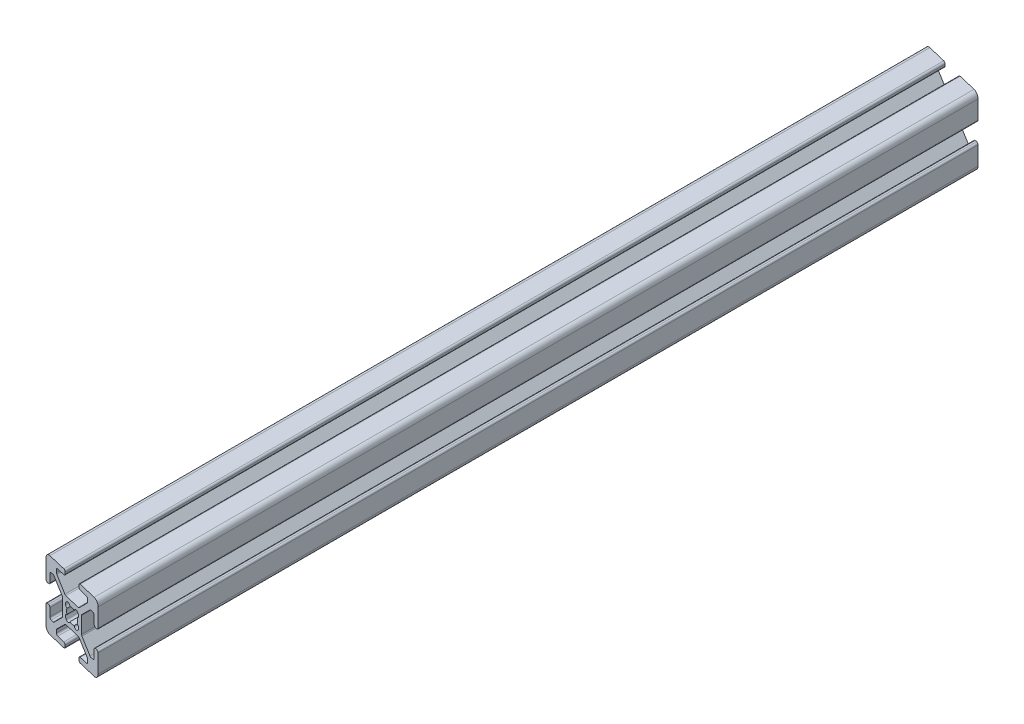
SolidWorks part; units mm, degrees
material "Alumina"
ref_plane "Front Plane" through (0, 0, 0) normal (0, 0, 1) x (1, 0, 0)
ref_plane "Top Plane" through (0, 0, 0) normal (0, 1, 0) x (1, 0, 0)
ref_plane "Right Plane" through (0, 0, 0) normal (1, 0, 0) x (0, 0, -1)
ref_plane "Plane1" through (0, 0, 4000) normal (0, 0, 1) x (1, 0, 0)
sketch "Sketch1" plane through (0, 0, 4000) normal (0, 0, 1) x (1, 0, 0)
  line B0 (10, 3.138) -> (10, 8.5)
  line B1 (8.5, 10) -> (3.138, 10)
  line B2 (2.63, 9.492) -> (2.63, 9.008)
  line B3 (3.138, 8.5) -> (5.487, 8.5)
  line B4 (5.995, 7.992) -> (5.995, 7.2661)
  line B5 (5.8462, 6.9069) -> (2.7431, 3.8038)
  line B6 (2.3839, 3.655) -> (-2.3839, 3.655)
  line B7 (-2.7431, 3.8038) -> (-5.8462, 6.9069)
  line B8 (-5.995, 7.2661) -> (-5.995, 7.992)
  line B9 (-5.487, 8.5) -> (-3.138, 8.5)
  line B10 (-2.63, 9.008) -> (-2.63, 9.492)
  line B11 (-3.138, 10) -> (-8.5, 10)
  line B12 (-10, 8.5) -> (-10, 3.138)
  line B13 (-9.492, 2.63) -> (-9.008, 2.63)
  line B14 (-8.5, 3.138) -> (-8.5, 5.487)
  line B15 (-7.992, 5.995) -> (-7.2661, 5.995)
  line B16 (-6.9069, 5.8462) -> (-3.8038, 2.7431)
  line B17 (-3.655, 2.3839) -> (-3.655, -2.3839)
  line B18 (-3.8038, -2.7431) -> (-6.9069, -5.8462)
  line B19 (-7.2661, -5.995) -> (-7.992, -5.995)
  line B20 (-8.5, -5.487) -> (-8.5, -3.138)
  line B21 (-9.008, -2.63) -> (-9.492, -2.63)
  line B22 (-10, -3.138) -> (-10, -8.5)
  line B23 (-8.5, -10) -> (-3.138, -10)
  line B24 (-2.63, -9.492) -> (-2.63, -9.008)
  line B25 (-3.138, -8.5) -> (-5.487, -8.5)
  line B26 (-5.995, -7.992) -> (-5.995, -7.2661)
  line B27 (-5.8462, -6.9069) -> (-2.7431, -3.8038)
  line B28 (-2.3839, -3.655) -> (2.3839, -3.655)
  line B29 (2.7431, -3.8038) -> (5.8462, -6.9069)
  line B30 (5.995, -7.2661) -> (5.995, -7.992)
  line B31 (5.487, -8.5) -> (3.138, -8.5)
  line B32 (2.63, -9.008) -> (2.63, -9.492)
  line B33 (3.138, -10) -> (8.5, -10)
  line B34 (10, -8.5) -> (10, -3.138)
  line B35 (9.492, -2.63) -> (9.008, -2.63)
  line B36 (8.5, -3.138) -> (8.5, -5.487)
  line B37 (7.992, -5.995) -> (7.2661, -5.995)
  line B38 (6.9069, -5.8462) -> (3.8038, -2.7431)
  line B39 (3.655, -2.3839) -> (3.655, 2.3839)
  line B40 (3.8038, 2.7431) -> (6.9069, 5.8462)
  line B41 (7.2661, 5.995) -> (7.992, 5.995)
  line B42 (8.5, 5.487) -> (8.5, 3.138)
  line B43 (9.008, 2.63) -> (9.492, 2.63)
  line B44 (-2.1249, -2.3045) -> (-2.3045, -2.1249)
  line B45 (-2.3045, 2.1249) -> (-2.1249, 2.3045)
  line B46 (2.1249, 2.3045) -> (2.3045, 2.1249)
  line B47 (2.3045, -2.1249) -> (2.1249, -2.3045)
  arc B48 (9.492, 2.63) -> (10, 3.138) centre (9.492, 3.138) ccw
  arc B49 (10, 8.5) -> (8.5, 10) centre (8.5, 8.5) ccw
  arc B50 (3.138, 10) -> (2.63, 9.492) centre (3.138, 9.492) ccw
  arc B51 (2.63, 9.008) -> (3.138, 8.5) centre (3.138, 9.008) ccw
  arc B52 (5.487, 8.5) -> (5.995, 7.992) centre (5.487, 7.992) cw
  arc B53 (5.995, 7.2661) -> (5.8462, 6.9069) centre (5.487, 7.2661) cw
  arc B54 (2.7431, 3.8038) -> (2.3839, 3.655) centre (2.3839, 4.163) cw
  arc B55 (-2.3839, 3.655) -> (-2.7431, 3.8038) centre (-2.3839, 4.163) cw
  arc B56 (-5.8462, 6.9069) -> (-5.995, 7.2661) centre (-5.487, 7.2661) cw
  arc B57 (-5.995, 7.992) -> (-5.487, 8.5) centre (-5.487, 7.992) cw
  arc B58 (-3.138, 8.5) -> (-2.63, 9.008) centre (-3.138, 9.008) ccw
  arc B59 (-2.63, 9.492) -> (-3.138, 10) centre (-3.138, 9.492) ccw
  arc B60 (-8.5, 10) -> (-10, 8.5) centre (-8.5, 8.5) ccw
  arc B61 (-10, 3.138) -> (-9.492, 2.63) centre (-9.492, 3.138) ccw
  arc B62 (-9.008, 2.63) -> (-8.5, 3.138) centre (-9.008, 3.138) ccw
  arc B63 (-8.5, 5.487) -> (-7.992, 5.995) centre (-7.992, 5.487) cw
  arc B64 (-7.2661, 5.995) -> (-6.9069, 5.8462) centre (-7.2661, 5.487) cw
  arc B65 (-3.8038, 2.7431) -> (-3.655, 2.3839) centre (-4.163, 2.3839) cw
  arc B66 (-3.655, -2.3839) -> (-3.8038, -2.7431) centre (-4.163, -2.3839) cw
  arc B67 (-6.9069, -5.8462) -> (-7.2661, -5.995) centre (-7.2661, -5.487) cw
  arc B68 (-7.992, -5.995) -> (-8.5, -5.487) centre (-7.992, -5.487) cw
  arc B69 (-8.5, -3.138) -> (-9.008, -2.63) centre (-9.008, -3.138) ccw
  arc B70 (-9.492, -2.63) -> (-10, -3.138) centre (-9.492, -3.138) ccw
  arc B71 (-10, -8.5) -> (-8.5, -10) centre (-8.5, -8.5) ccw
  arc B72 (-3.138, -10) -> (-2.63, -9.492) centre (-3.138, -9.492) ccw
  arc B73 (-2.63, -9.008) -> (-3.138, -8.5) centre (-3.138, -9.008) ccw
  arc B74 (-5.487, -8.5) -> (-5.995, -7.992) centre (-5.487, -7.992) cw
  arc B75 (-5.995, -7.2661) -> (-5.8462, -6.9069) centre (-5.487, -7.2661) cw
  arc B76 (-2.7431, -3.8038) -> (-2.3839, -3.655) centre (-2.3839, -4.163) cw
  arc B77 (2.3839, -3.655) -> (2.7431, -3.8038) centre (2.3839, -4.163) cw
  arc B78 (5.8462, -6.9069) -> (5.995, -7.2661) centre (5.487, -7.2661) cw
  arc B79 (5.995, -7.992) -> (5.487, -8.5) centre (5.487, -7.992) cw
  arc B80 (3.138, -8.5) -> (2.63, -9.008) centre (3.138, -9.008) ccw
  arc B81 (2.63, -9.492) -> (3.138, -10) centre (3.138, -9.492) ccw
  arc B82 (8.5, -10) -> (10, -8.5) centre (8.5, -8.5) ccw
  arc B83 (10, -3.138) -> (9.492, -2.63) centre (9.492, -3.138) ccw
  arc B84 (9.008, -2.63) -> (8.5, -3.138) centre (9.008, -3.138) ccw
  arc B85 (8.5, -5.487) -> (7.992, -5.995) centre (7.992, -5.487) cw
  arc B86 (7.2661, -5.995) -> (6.9069, -5.8462) centre (7.2661, -5.487) cw
  arc B87 (3.8038, -2.7431) -> (3.655, -2.3839) centre (4.163, -2.3839) cw
  arc B88 (3.655, 2.3839) -> (3.8038, 2.7431) centre (4.163, 2.3839) cw
  arc B89 (6.9069, 5.8462) -> (7.2661, 5.995) centre (7.2661, 5.487) cw
  arc B90 (7.992, 5.995) -> (8.5, 5.487) centre (7.992, 5.487) cw
  arc B91 (8.5, 3.138) -> (9.008, 2.63) centre (9.008, 3.138) ccw
  arc B92 (0.804, -1.9351) -> (-0.804, -1.9351) centre (0, 0) cw
  arc B93 (-0.804, -1.9351) -> (-2.1249, -2.3045) centre (-1.5684, -1.748) cw
  arc B94 (-2.3045, -2.1249) -> (-1.9351, -0.804) centre (-1.748, -1.5684) cw
  arc B95 (-1.9351, -0.804) -> (-1.9351, 0.804) centre (0, 0) cw
  arc B96 (-1.9351, 0.804) -> (-2.3045, 2.1249) centre (-1.748, 1.5684) cw
  arc B97 (-2.1249, 2.3045) -> (-0.804, 1.9351) centre (-1.5684, 1.748) cw
  arc B98 (-0.804, 1.9351) -> (0.804, 1.9351) centre (0, 0) cw
  arc B99 (0.804, 1.9351) -> (2.1249, 2.3045) centre (1.5684, 1.748) cw
  arc B100 (2.3045, 2.1249) -> (1.9351, 0.804) centre (1.748, 1.5684) cw
  arc B101 (1.9351, 0.804) -> (1.9351, -0.804) centre (0, 0) cw
  arc B102 (1.9351, -0.804) -> (2.3045, -2.1249) centre (1.748, -1.5684) cw
  arc B103 (2.1249, -2.3045) -> (0.804, -1.9351) centre (1.5684, -1.748) cw
sketch_block_instance "Block1-1"
sketch_block "Block1"
extrude "Boss-Extrude1" add sketch "Sketch1" against normal blind 261.8
sketch "Sketch2" plane through (0, -10, 0) normal (0, -1, 0) x (1, 0, 0)
  line L0 (10, 4000) -> (-10, 3995.2132)
  line L1 (55, 4000) -> (-55, 4000) construction
  line L2 (10, 3738.2) -> (10, 4000) construction
  line L3 (-10, 3738.2) -> (-10, 4000) construction
  line L4 (-10, 3995.2132) -> (-10, 4000)
  line L5 (-10, 4000) -> (10, 4000)
  line L6 (10, 3738.2) -> (10, 3742.9868)
  line L7 (10, 3742.9868) -> (-10, 3738.2)
  line L8 (-10, 3738.2) -> (10, 3738.2)
  dimension "D1" = 76.54
  dimension "D2" = 76.54
extrude "Cut-Extrude1" cut sketch "Sketch2" against normal through all
